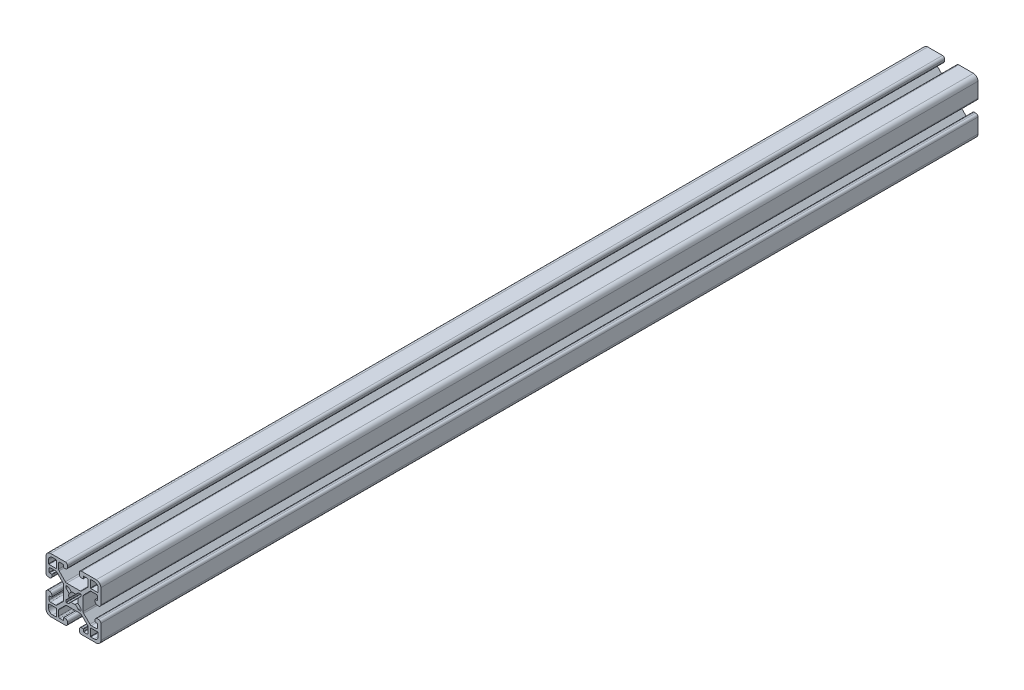
SolidWorks part; units mm, degrees
ref_plane "Front Plane" through (0, 0, 0) normal (0, 0, 1) x (1, 0, 0)
ref_plane "Top Plane" through (0, 0, 0) normal (0, 1, 0) x (1, 0, 0)
ref_plane "Right Plane" through (0, 0, 0) normal (1, 0, 0) x (0, 0, -1)
ref_plane "Plane1" through (0, 0, -609.6) normal (0, 0, -1) x (-1, 0, 0)
sketch "Sketch1" plane through (0, 0, -609.6) normal (0, 0, -1) x (-1, 0, 0)
  line L0 (17.2603, 14.4663) -> (17.2603, 12.1295)
  line L1 (17.0063, 11.8755) -> (12.1295, 11.8755)
  line L2 (11.8755, 12.1295) -> (11.8755, 17.0063)
  line L3 (12.1295, 17.2603) -> (14.4663, 17.2603)
  line L4 (17.2603, -12.1295) -> (17.2603, -14.4663)
  line L5 (14.4663, -17.2603) -> (12.1295, -17.2603)
  line L6 (11.8755, -17.0063) -> (11.8755, -12.1295)
  line L7 (12.1295, -11.8755) -> (17.0063, -11.8755)
  line L8 (5.1689, -3.9207) -> (5.1689, -4.9149)
  line L9 (4.9149, -5.1689) -> (3.9207, -5.1689)
  line L10 (3.2921, -4.9085) -> (1.4014, -3.0179)
  line L11 (-1.4014, -3.0179) -> (-3.2921, -4.9085)
  line L12 (-3.9207, -5.1689) -> (-4.9149, -5.1689)
  line L13 (-5.1689, -4.9149) -> (-5.1689, -3.9207)
  line L14 (-4.9085, -3.2921) -> (-3.0179, -1.4014)
  line L15 (-3.0179, 1.4014) -> (-4.9085, 3.2921)
  line L16 (-5.1689, 3.9207) -> (-5.1689, 4.9149)
  line L17 (-4.9149, 5.1689) -> (-3.9207, 5.1689)
  line L18 (-3.2921, 4.9085) -> (-1.4014, 3.0179)
  line L19 (1.4014, 3.0179) -> (3.2921, 4.9085)
  line L20 (3.9207, 5.1689) -> (4.9149, 5.1689)
  line L21 (5.1689, 4.9149) -> (5.1689, 3.9207)
  line L22 (4.9085, 3.2921) -> (3.0179, 1.4014)
  line L23 (3.0179, -1.4014) -> (4.9085, -3.2921)
  line L24 (-11.8755, -12.1295) -> (-11.8755, -17.0063)
  line L25 (-12.1295, -17.2603) -> (-14.4663, -17.2603)
  line L26 (-17.2603, -14.4663) -> (-17.2603, -12.1295)
  line L27 (-17.0063, -11.8755) -> (-12.1295, -11.8755)
  line L28 (-11.8755, 17.0063) -> (-11.8755, 12.1295)
  line L29 (-12.1295, 11.8755) -> (-17.0063, 11.8755)
  line L30 (-17.2603, 12.1295) -> (-17.2603, 14.4663)
  line L31 (-14.4663, 17.2603) -> (-12.1295, 17.2603)
  line L32 (17.4752, -4.064) -> (16.5608, -4.064)
  line L33 (14.986, -5.6388) -> (14.986, -6.6177)
  line L34 (15.24, -6.8717) -> (16.5862, -6.8717)
  line L35 (16.8402, -7.1257) -> (16.8402, -9.4117)
  line L36 (15.9512, -10.3007) -> (12.3894, -10.3007)
  line L37 (11.4913, -9.9288) -> (7.1157, -5.5531)
  line L38 (6.7437, -4.6551) -> (6.7437, 4.6551)
  line L39 (7.1157, 5.5531) -> (11.4913, 9.9288)
  line L40 (12.3894, 10.3007) -> (15.9512, 10.3007)
  line L41 (16.8402, 9.4117) -> (16.8402, 7.1257)
  line L42 (16.5862, 6.8717) -> (15.24, 6.8717)
  line L43 (14.986, 6.6177) -> (14.986, 5.6388)
  line L44 (16.5608, 4.064) -> (17.4752, 4.064)
  line L45 (19.05, 5.6388) -> (19.05, 15.875)
  line L46 (15.875, 19.05) -> (5.6388, 19.05)
  line L47 (4.064, 17.4752) -> (4.064, 16.5608)
  line L48 (5.6388, 14.986) -> (6.6177, 14.986)
  line L49 (6.8717, 15.24) -> (6.8717, 16.5862)
  line L50 (7.1257, 16.8402) -> (9.4117, 16.8402)
  line L51 (10.3007, 15.9512) -> (10.3007, 12.3894)
  line L52 (9.9288, 11.4913) -> (5.5531, 7.1157)
  line L53 (4.6551, 6.7437) -> (-4.6551, 6.7437)
  line L54 (-5.5531, 7.1157) -> (-9.9288, 11.4913)
  line L55 (-10.3007, 12.3894) -> (-10.3007, 15.9512)
  line L56 (-9.4117, 16.8402) -> (-7.1257, 16.8402)
  line L57 (-6.8717, 16.5862) -> (-6.8717, 15.24)
  line L58 (-6.6177, 14.986) -> (-5.6388, 14.986)
  line L59 (-4.064, 16.5608) -> (-4.064, 17.4752)
  line L60 (-5.6388, 19.05) -> (-15.875, 19.05)
  line L61 (-19.05, 15.875) -> (-19.05, 5.6388)
  line L62 (-17.4752, 4.064) -> (-16.5608, 4.064)
  line L63 (-14.986, 5.6388) -> (-14.986, 6.6177)
  line L64 (-15.24, 6.8717) -> (-16.5862, 6.8717)
  line L65 (-16.8402, 7.1257) -> (-16.8402, 9.4117)
  line L66 (-15.9512, 10.3007) -> (-12.3894, 10.3007)
  line L67 (-11.4913, 9.9288) -> (-7.1157, 5.5531)
  line L68 (-6.7437, 4.6551) -> (-6.7437, -4.6551)
  line L69 (-7.1157, -5.5531) -> (-11.4913, -9.9288)
  line L70 (-12.3894, -10.3007) -> (-15.9512, -10.3007)
  line L71 (-16.8402, -9.4117) -> (-16.8402, -7.1257)
  line L72 (-16.5862, -6.8717) -> (-15.24, -6.8717)
  line L73 (-14.986, -6.6177) -> (-14.986, -5.6388)
  line L74 (-16.5608, -4.064) -> (-17.4752, -4.064)
  line L75 (-19.05, -5.6388) -> (-19.05, -15.875)
  line L76 (-15.875, -19.05) -> (-5.6388, -19.05)
  line L77 (-4.064, -17.4752) -> (-4.064, -16.5608)
  line L78 (-5.6388, -14.986) -> (-6.6177, -14.986)
  line L79 (-6.8717, -15.24) -> (-6.8717, -16.5862)
  line L80 (-7.1257, -16.8402) -> (-9.4117, -16.8402)
  line L81 (-10.3007, -15.9512) -> (-10.3007, -12.3894)
  line L82 (-9.9288, -11.4913) -> (-5.5531, -7.1157)
  line L83 (-4.6551, -6.7437) -> (4.6551, -6.7437)
  line L84 (5.5531, -7.1157) -> (9.9288, -11.4913)
  line L85 (10.3007, -12.3894) -> (10.3007, -15.9512)
  line L86 (9.4117, -16.8402) -> (7.1257, -16.8402)
  line L87 (6.8717, -16.5862) -> (6.8717, -15.24)
  line L88 (6.6177, -14.986) -> (5.6388, -14.986)
  line L89 (4.064, -16.5608) -> (4.064, -17.4752)
  line L90 (5.6388, -19.05) -> (15.875, -19.05)
  line L91 (19.05, -15.875) -> (19.05, -5.6388)
  arc A0 (17.2603, 12.1295) -> (17.0063, 11.8755) centre (17.0063, 12.1295) cw
  arc A1 (12.1295, 11.8755) -> (11.8755, 12.1295) centre (12.1295, 12.1295) cw
  arc A2 (11.8755, 17.0063) -> (12.1295, 17.2603) centre (12.1295, 17.0063) cw
  arc A3 (14.4663, 17.2603) -> (17.2603, 14.4663) centre (14.4663, 14.4663) cw
  arc A4 (17.2603, -14.4663) -> (14.4663, -17.2603) centre (14.4663, -14.4663) cw
  arc A5 (12.1295, -17.2603) -> (11.8755, -17.0063) centre (12.1295, -17.0063) cw
  arc A6 (11.8755, -12.1295) -> (12.1295, -11.8755) centre (12.1295, -12.1295) cw
  arc A7 (17.0063, -11.8755) -> (17.2603, -12.1295) centre (17.0063, -12.1295) cw
  arc A8 (5.1689, -4.9149) -> (4.9149, -5.1689) centre (4.9149, -4.9149) cw
  arc A9 (3.9207, -5.1689) -> (3.2921, -4.9085) centre (3.9207, -4.2799) cw
  arc A10 (1.4014, -3.0179) -> (-1.4014, -3.0179) centre (0, 0) cw
  arc A11 (-3.2921, -4.9085) -> (-3.9207, -5.1689) centre (-3.9207, -4.2799) cw
  arc A12 (-4.9149, -5.1689) -> (-5.1689, -4.9149) centre (-4.9149, -4.9149) cw
  arc A13 (-5.1689, -3.9207) -> (-4.9085, -3.2921) centre (-4.2799, -3.9207) cw
  arc A14 (-3.0179, -1.4014) -> (-3.0179, 1.4014) centre (0, 0) cw
  arc A15 (-4.9085, 3.2921) -> (-5.1689, 3.9207) centre (-4.2799, 3.9207) cw
  arc A16 (-5.1689, 4.9149) -> (-4.9149, 5.1689) centre (-4.9149, 4.9149) cw
  arc A17 (-3.9207, 5.1689) -> (-3.2921, 4.9085) centre (-3.9207, 4.2799) cw
  arc A18 (-1.4014, 3.0179) -> (1.4014, 3.0179) centre (0, 0) cw
  arc A19 (3.2921, 4.9085) -> (3.9207, 5.1689) centre (3.9207, 4.2799) cw
  arc A20 (4.9149, 5.1689) -> (5.1689, 4.9149) centre (4.9149, 4.9149) cw
  arc A21 (5.1689, 3.9207) -> (4.9085, 3.2921) centre (4.2799, 3.9207) cw
  arc A22 (3.0179, 1.4014) -> (3.0179, -1.4014) centre (0, 0) cw
  arc A23 (4.9085, -3.2921) -> (5.1689, -3.9207) centre (4.2799, -3.9207) cw
  arc A24 (-12.1295, -11.8755) -> (-11.8755, -12.1295) centre (-12.1295, -12.1295) cw
  arc A25 (-11.8755, -17.0063) -> (-12.1295, -17.2603) centre (-12.1295, -17.0063) cw
  arc A26 (-14.4663, -17.2603) -> (-17.2603, -14.4663) centre (-14.4663, -14.4663) cw
  arc A27 (-17.2603, -12.1295) -> (-17.0063, -11.8755) centre (-17.0063, -12.1295) cw
  arc A28 (-12.1295, 17.2603) -> (-11.8755, 17.0063) centre (-12.1295, 17.0063) cw
  arc A29 (-11.8755, 12.1295) -> (-12.1295, 11.8755) centre (-12.1295, 12.1295) cw
  arc A30 (-17.0063, 11.8755) -> (-17.2603, 12.1295) centre (-17.0063, 12.1295) cw
  arc A31 (-17.2603, 14.4663) -> (-14.4663, 17.2603) centre (-14.4663, 14.4663) cw
  arc A32 (19.05, -5.6388) -> (17.4752, -4.064) centre (17.4752, -5.6388) ccw
  arc A33 (16.5608, -4.064) -> (14.986, -5.6388) centre (16.5608, -5.6388) ccw
  arc A34 (14.986, -6.6177) -> (15.24, -6.8717) centre (15.24, -6.6177) ccw
  arc A35 (16.5862, -6.8717) -> (16.8402, -7.1257) centre (16.5862, -7.1257) cw
  arc A36 (16.8402, -9.4117) -> (15.9512, -10.3007) centre (15.9512, -9.4117) cw
  arc A37 (12.3894, -10.3007) -> (11.4913, -9.9288) centre (12.3894, -9.0307) cw
  arc A38 (7.1157, -5.5531) -> (6.7437, -4.6551) centre (8.0137, -4.6551) cw
  arc A39 (6.7437, 4.6551) -> (7.1157, 5.5531) centre (8.0137, 4.6551) cw
  arc A40 (11.4913, 9.9288) -> (12.3894, 10.3007) centre (12.3894, 9.0307) cw
  arc A41 (15.9512, 10.3007) -> (16.8402, 9.4117) centre (15.9512, 9.4117) cw
  arc A42 (16.8402, 7.1257) -> (16.5862, 6.8717) centre (16.5862, 7.1257) cw
  arc A43 (15.24, 6.8717) -> (14.986, 6.6177) centre (15.24, 6.6177) ccw
  arc A44 (14.986, 5.6388) -> (16.5608, 4.064) centre (16.5608, 5.6388) ccw
  arc A45 (17.4752, 4.064) -> (19.05, 5.6388) centre (17.4752, 5.6388) ccw
  arc A46 (19.05, 15.875) -> (15.875, 19.05) centre (15.875, 15.875) ccw
  arc A47 (5.6388, 19.05) -> (4.064, 17.4752) centre (5.6388, 17.4752) ccw
  arc A48 (4.064, 16.5608) -> (5.6388, 14.986) centre (5.6388, 16.5608) ccw
  arc A49 (6.6177, 14.986) -> (6.8717, 15.24) centre (6.6177, 15.24) ccw
  arc A50 (6.8717, 16.5862) -> (7.1257, 16.8402) centre (7.1257, 16.5862) cw
  arc A51 (9.4117, 16.8402) -> (10.3007, 15.9512) centre (9.4117, 15.9512) cw
  arc A52 (10.3007, 12.3894) -> (9.9288, 11.4913) centre (9.0307, 12.3894) cw
  arc A53 (5.5531, 7.1157) -> (4.6551, 6.7437) centre (4.6551, 8.0137) cw
  arc A54 (-4.6551, 6.7437) -> (-5.5531, 7.1157) centre (-4.6551, 8.0137) cw
  arc A55 (-9.9288, 11.4913) -> (-10.3007, 12.3894) centre (-9.0307, 12.3894) cw
  arc A56 (-10.3007, 15.9512) -> (-9.4117, 16.8402) centre (-9.4117, 15.9512) cw
  arc A57 (-7.1257, 16.8402) -> (-6.8717, 16.5862) centre (-7.1257, 16.5862) cw
  arc A58 (-6.8717, 15.24) -> (-6.6177, 14.986) centre (-6.6177, 15.24) ccw
  arc A59 (-5.6388, 14.986) -> (-4.064, 16.5608) centre (-5.6388, 16.5608) ccw
  arc A60 (-4.064, 17.4752) -> (-5.6388, 19.05) centre (-5.6388, 17.4752) ccw
  arc A61 (-15.875, 19.05) -> (-19.05, 15.875) centre (-15.875, 15.875) ccw
  arc A62 (-19.05, 5.6388) -> (-17.4752, 4.064) centre (-17.4752, 5.6388) ccw
  arc A63 (-16.5608, 4.064) -> (-14.986, 5.6388) centre (-16.5608, 5.6388) ccw
  arc A64 (-14.986, 6.6177) -> (-15.24, 6.8717) centre (-15.24, 6.6177) ccw
  arc A65 (-16.5862, 6.8717) -> (-16.8402, 7.1257) centre (-16.5862, 7.1257) cw
  arc A66 (-16.8402, 9.4117) -> (-15.9512, 10.3007) centre (-15.9512, 9.4117) cw
  arc A67 (-12.3894, 10.3007) -> (-11.4913, 9.9288) centre (-12.3894, 9.0307) cw
  arc A68 (-7.1157, 5.5531) -> (-6.7437, 4.6551) centre (-8.0137, 4.6551) cw
  arc A69 (-6.7437, -4.6551) -> (-7.1157, -5.5531) centre (-8.0137, -4.6551) cw
  arc A70 (-11.4913, -9.9288) -> (-12.3894, -10.3007) centre (-12.3894, -9.0307) cw
  arc A71 (-15.9512, -10.3007) -> (-16.8402, -9.4117) centre (-15.9512, -9.4117) cw
  arc A72 (-16.8402, -7.1257) -> (-16.5862, -6.8717) centre (-16.5862, -7.1257) cw
  arc A73 (-15.24, -6.8717) -> (-14.986, -6.6177) centre (-15.24, -6.6177) ccw
  arc A74 (-14.986, -5.6388) -> (-16.5608, -4.064) centre (-16.5608, -5.6388) ccw
  arc A75 (-17.4752, -4.064) -> (-19.05, -5.6388) centre (-17.4752, -5.6388) ccw
  arc A76 (-19.05, -15.875) -> (-15.875, -19.05) centre (-15.875, -15.875) ccw
  arc A77 (-5.6388, -19.05) -> (-4.064, -17.4752) centre (-5.6388, -17.4752) ccw
  arc A78 (-4.064, -16.5608) -> (-5.6388, -14.986) centre (-5.6388, -16.5608) ccw
  arc A79 (-6.6177, -14.986) -> (-6.8717, -15.24) centre (-6.6177, -15.24) ccw
  arc A80 (-6.8717, -16.5862) -> (-7.1257, -16.8402) centre (-7.1257, -16.5862) cw
  arc A81 (-9.4117, -16.8402) -> (-10.3007, -15.9512) centre (-9.4117, -15.9512) cw
  arc A82 (-10.3007, -12.3894) -> (-9.9288, -11.4913) centre (-9.0307, -12.3894) cw
  arc A83 (-5.5531, -7.1157) -> (-4.6551, -6.7437) centre (-4.6551, -8.0137) cw
  arc A84 (4.6551, -6.7437) -> (5.5531, -7.1157) centre (4.6551, -8.0137) cw
  arc A85 (9.9288, -11.4913) -> (10.3007, -12.3894) centre (9.0307, -12.3894) cw
  arc A86 (10.3007, -15.9512) -> (9.4117, -16.8402) centre (9.4117, -15.9512) cw
  arc A87 (7.1257, -16.8402) -> (6.8717, -16.5862) centre (7.1257, -16.5862) cw
  arc A88 (6.8717, -15.24) -> (6.6177, -14.986) centre (6.6177, -15.24) ccw
  arc A89 (5.6388, -14.986) -> (4.064, -16.5608) centre (5.6388, -16.5608) ccw
  arc A90 (4.064, -17.4752) -> (5.6388, -19.05) centre (5.6388, -17.4752) ccw
  arc A91 (15.875, -19.05) -> (19.05, -15.875) centre (15.875, -15.875) ccw
extrude "Boss-Extrude1" add sketch "Sketch1" against normal blind 609.6
